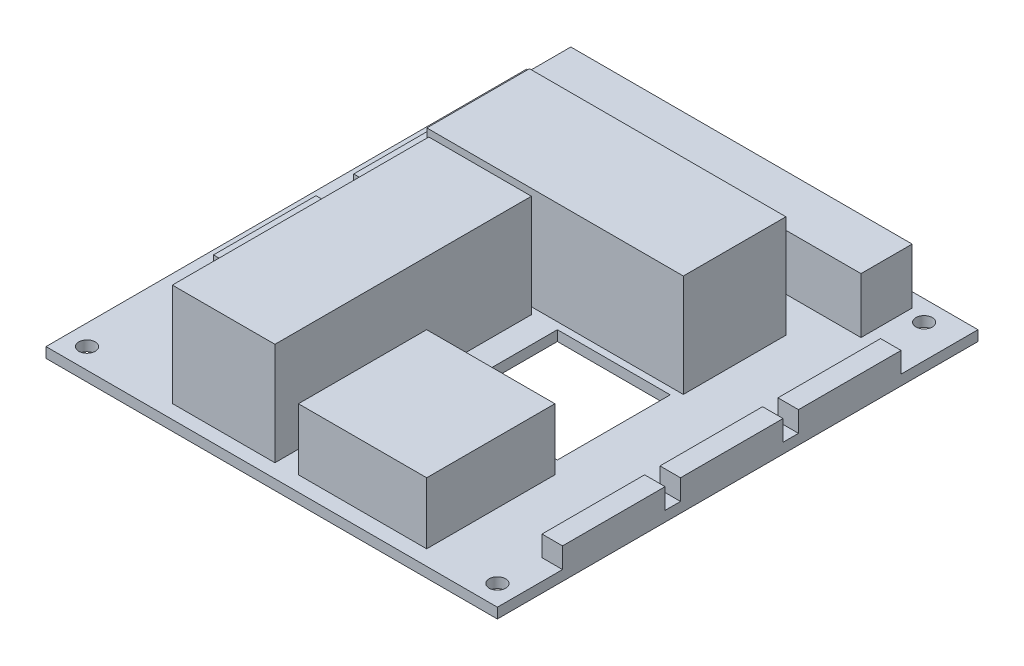
SolidWorks part; units mm, degrees
material "PBT General Purpose"
ref_plane "Front Plane" through (0, 0, 0) normal (0, 0, 1) x (1, 0, 0)
ref_plane "Top Plane" through (0, 0, 0) normal (0, 1, 0) x (1, 0, 0)
ref_plane "Right Plane" through (0, 0, 0) normal (1, 0, 0) x (0, 0, -1)
sketch "Sketch1" plane through (0, 0, 0) normal (0, 1, 0) x (1, 0, 0)
  line L1 (50, -50) -> (-50, -50) construction
  line L2 (50, -50) -> (50, 50) construction
  line L3 (50, 50) -> (-50, 50) construction
  line L4 (-50, -50) -> (-50, 50) construction
  line L5 (50, -50) -> (-50, 50) construction
  line L6 (50, 50) -> (-50, -50) construction
  line L7 (-50, 50) -> (-44, 50) construction
  line L8 (-50, 50) -> (-50, 44) construction
  line L9 (-50, 44) -> (-44, 44) construction
  line L10 (-44, 50) -> (-44, 44) construction
  line L11 (-50, -50) -> (-44, -50) construction
  line L12 (-50, -50) -> (-50, -44) construction
  line L13 (-50, -44) -> (-44, -44) construction
  line L14 (-44, -50) -> (-44, -44) construction
  line L15 (50, -50) -> (44, -50) construction
  line L16 (50, -50) -> (50, -44) construction
  line L17 (50, -44) -> (44, -44) construction
  line L18 (44, -50) -> (44, -44) construction
  line L19 (50, 50) -> (44, 50) construction
  line L20 (50, 50) -> (50, 44) construction
  line L21 (50, 44) -> (44, 44) construction
  line L22 (44, 50) -> (44, 44) construction
  line L25 (-32.625, 44.091) -> (33.923, 44.091) construction
  line L26 (-32.625, 44.091) -> (-32.625, 34.112) construction
  line L27 (-32.625, 34.112) -> (33.923, 34.112) construction
  line L28 (33.923, 44.091) -> (33.923, 34.112) construction
  line L30 (-50, 50) -> (-35, 50)
  line L31 (-50, 50) -> (-50, 48)
  line L32 (-50, 48) -> (-35, 48)
  line L33 (-35, 50) -> (-35, 48)
  line L34 (-50, 50) -> (-48, 50)
  line L35 (-50, 50) -> (-50, 35)
  line L36 (-50, 35) -> (-48, 35)
  line L37 (-48, 50) -> (-48, 35)
  line L38 (50, 50) -> (35, 50)
  line L39 (50, 50) -> (50, 48)
  line L40 (50, 48) -> (35, 48)
  line L41 (35, 50) -> (35, 48)
  line L42 (50, 50) -> (48, 50)
  line L43 (50, 50) -> (50, 35)
  line L44 (50, 35) -> (48, 35)
  line L45 (48, 50) -> (48, 35)
  line L46 (50, -50) -> (48, -50)
  line L47 (50, -50) -> (50, -35)
  line L48 (50, -35) -> (48, -35)
  line L49 (48, -50) -> (48, -35)
  line L50 (50, -50) -> (35, -50)
  line L51 (50, -50) -> (50, -48)
  line L52 (50, -48) -> (35, -48)
  line L53 (35, -50) -> (35, -48)
  line L54 (-50, -50) -> (-35, -50)
  line L55 (-50, -50) -> (-50, -48)
  line L56 (-50, -48) -> (-35, -48)
  line L57 (-35, -50) -> (-35, -48)
  line L58 (-50, -50) -> (-48, -50)
  line L59 (-50, -50) -> (-50, -35)
  line L60 (-50, -35) -> (-48, -35)
  line L61 (-48, -50) -> (-48, -35)
  line L62 (-33.125, 44.591) -> (-33.125, 33.612)
  line L63 (-33.125, 33.612) -> (34.423, 33.612)
  line L64 (34.423, 44.591) -> (34.423, 33.612)
  line L65 (-33.125, 44.591) -> (34.423, 44.591)
  circle A0 centre (-36.2, 42.85) radius 1.6
  circle A1 centre (37.5, 42.85) radius 1.6
  circle A2 centre (40, -42.85) radius 1.6
  circle A3 centre (-40, -42.85) radius 1.6
  point P0 (0, 0)
  point P5 (0, 0)
  point P6 (0, 0)
  dimension "D7" = 3.2
  dimension "D1" = 100
  dimension "D2" = 100
  dimension "D3" = 6
  dimension "D4" = 6
  dimension "D5" = 6
  dimension "D6" = 6
  dimension "D8" = 7.15
  dimension "D9" = 13.8
  dimension "D10" = 10
  dimension "D11" = 7.15
  dimension "D12" = 10
  dimension "D13" = 7.15
  dimension "D14" = 17.375
  dimension "D15" = 5.909
  dimension "D16" = 15.888
  dimension "D17" = 16.077
  dimension "D18" = 73.7
  dimension "D19" = 15
  dimension "D20" = 2
  dimension "D21" = 15
  dimension "D22" = 2
  dimension "D23" = 2
  dimension "D24" = 15
  dimension "D25" = 15
  dimension "D26" = 2
  dimension "D27" = 15
  dimension "D28" = 2
  dimension "D29" = 2
  dimension "D30" = 15
  dimension "D31" = 15
  dimension "D32" = 15
  dimension "D33" = 2
  dimension "D34" = 2
  dimension "D35" = 0.5
sketch "Sketch2" plane through (0, 0, 0) normal (0, 1, 0) x (1, 0, 0)
  line L0 (33.923, 44.091) -> (33.923, 34.112) construction
  line L1 (-32.625, 34.112) -> (33.923, 34.112) construction
  line L2 (-32.625, 44.091) -> (33.923, 44.091) construction
  line L3 (-32.625, 44.091) -> (-32.625, 34.112) construction
  line L4 (33.923, 44.091) -> (33.923, 34.112)
  line L5 (-32.625, 34.112) -> (33.923, 34.112)
  line L6 (-32.625, 44.091) -> (33.923, 44.091)
  line L7 (-32.625, 44.091) -> (-32.625, 34.112)
  line L8 (3, 5.85) -> (25, 5.85)
  line L9 (-22.0688, 5.85) -> (-2.0688, 5.85)
  line L10 (-22.0688, 5.85) -> (-22.0688, -44.15)
  line L11 (-22.0688, -44.15) -> (-2.0688, -44.15)
  line L12 (-2.0688, 5.85) -> (-2.0688, -44.15)
  line L13 (-23.7903, 27.1915) -> (26.2097, 27.1915)
  line L14 (-23.7903, 27.1915) -> (-23.7903, 7.1915)
  line L15 (-23.7903, 7.1915) -> (26.2097, 7.1915)
  line L16 (26.2097, 27.1915) -> (26.2097, 7.1915)
  line L17 (4, 4.85) -> (24, 4.85)
  line L18 (4, 4.85) -> (4, -15.15)
  line L19 (4, -15.15) -> (24, -15.15)
  line L20 (24, 4.85) -> (24, -15.15)
  line L21 (25, 5.85) -> (25, -16.15)
  line L22 (3, -16.15) -> (25, -16.15)
  line L23 (3, 5.85) -> (3, -16.15)
  line L24 (40, 8.85) -> (44, 8.85)
  line L25 (40, 31.85) -> (44, 31.85)
  line L26 (40, 31.85) -> (40, 11.85)
  line L27 (40, 11.85) -> (44, 11.85)
  line L28 (44, 31.85) -> (44, 11.85)
  line L29 (40, 8.85) -> (40, -11.15)
  line L30 (40, -11.15) -> (44, -11.15)
  line L31 (44, 8.85) -> (44, -11.15)
  line L32 (40, -14.15) -> (44, -14.15)
  line L33 (40, -14.15) -> (40, -34.15)
  line L34 (40, -34.15) -> (44, -34.15)
  line L35 (44, -14.15) -> (44, -34.15)
  line L37 (2.2571, -18.8919) -> (27.2571, -18.8919)
  line L38 (2.2571, -18.8919) -> (2.2571, -43.8919)
  line L39 (2.2571, -43.8919) -> (27.2571, -43.8919)
  line L40 (27.2571, -18.8919) -> (27.2571, -43.8919)
  line L41 (44, -46.85) -> (-44, -46.85) construction
  line L42 (44, -46.85) -> (44, 46.85) construction
  line L43 (44, 46.85) -> (-44, 46.85) construction
  line L44 (-44, -46.85) -> (-44, 46.85) construction
  line L45 (44, -46.85) -> (-44, 46.85) construction
  line L46 (44, 46.85) -> (-44, -46.85) construction
  circle A0 centre (40, -42.85) radius 1.6 construction
  circle A1 centre (-40, -42.85) radius 1.6 construction
  circle A2 centre (37.5, 42.85) radius 1.6 construction
  circle A3 centre (-36.2, 42.85) radius 1.6 construction
  circle A4 centre (40, -42.85) radius 1.6
  circle A5 centre (-40, -42.85) radius 1.6
  circle A6 centre (37.5, 42.85) radius 1.6
  circle A7 centre (-36.2, 42.85) radius 1.6
  point P32 (0, 0)
  dimension "D1" = 20
  dimension "D2" = 50
  dimension "D3" = 50
  dimension "D4" = 20
  dimension "D6" = 4
  dimension "D7" = 20
  dimension "D9" = 25
  dimension "D10" = 4
  dimension "D11" = 4
  dimension "D12" = 42
  dimension "D13" = 20
  dimension "D14" = 15
  dimension "D15" = 88
  dimension "D16" = 93.7
  dimension "D5" = 1
  dimension "D8" = 3
sketch "Sketch3" plane through (0, 0, 0) normal (0, 1, 0) x (1, 0, 0)
  line L0 (25, 5.85) -> (25, -16.15) construction
  line L1 (3, 5.85) -> (25, 5.85) construction
  line L2 (3, 5.85) -> (3, -16.15) construction
  line L3 (3, -16.15) -> (25, -16.15) construction
  line L4 (44, -46.85) -> (-44, -46.85) construction
  line L5 (44, -46.85) -> (44, 46.85) construction
  line L6 (44, 46.85) -> (-44, 46.85) construction
  line L7 (-44, -46.85) -> (-44, 46.85) construction
  line L8 (25, 5.85) -> (25, -16.15)
  line L9 (3, 5.85) -> (25, 5.85)
  line L10 (3, 5.85) -> (3, -16.15)
  line L11 (3, -16.15) -> (25, -16.15)
  line L12 (44, -46.85) -> (-44, -46.85)
  line L13 (44, -46.85) -> (44, 46.85)
  line L14 (44, 46.85) -> (-44, 46.85)
  line L15 (-44, -46.85) -> (-44, 46.85)
  circle A0 centre (-40, -42.85) radius 1.6 construction
  circle A1 centre (40, -42.85) radius 1.6 construction
  circle A2 centre (37.5, 42.85) radius 1.6 construction
  circle A3 centre (-36.2, 42.85) radius 1.6 construction
  circle A4 centre (-40, -42.85) radius 1.6
  circle A5 centre (40, -42.85) radius 1.6
  circle A6 centre (37.5, 42.85) radius 1.6
  circle A7 centre (-36.2, 42.85) radius 1.6
extrude "Boss-Extrude1" add sketch "Sketch3" along normal blind 2
sketch "Sketch4" plane through (0, 2, 0) normal (0, 1, 0) x (1, 0, 0)
  line L0 (-32.625, 44.091) -> (-32.625, 34.112) construction
  line L1 (-32.625, 34.112) -> (33.923, 34.112) construction
  line L2 (33.923, 44.091) -> (33.923, 34.112) construction
  line L3 (-32.625, 44.091) -> (33.923, 44.091) construction
  line L12 (-32.625, 44.091) -> (-32.625, 34.112)
  line L13 (-32.625, 34.112) -> (33.923, 34.112)
  line L14 (33.923, 44.091) -> (33.923, 34.112)
  line L15 (-32.625, 44.091) -> (33.923, 44.091)
extrude "Boss-Extrude2" add sketch "Sketch4" along normal blind 10.8 separate body
sketch "Sketch5" plane through (0, 2, 0) normal (0, -1, 0) x (1, 0, 0)
  line L0 (-32.625, -34.112) -> (33.923, -34.112) construction
  line L1 (-31.672, -35.065) -> (-31.037, -35.065)
  line L2 (-31.672, -35.065) -> (-31.672, -35.7)
  line L3 (-31.672, -35.7) -> (-31.037, -35.7)
  line L4 (-31.037, -35.065) -> (-31.037, -35.7)
  line L5 (-31.672, -35.065) -> (-31.037, -35.7) construction
  line L6 (-31.672, -35.7) -> (-31.037, -35.065) construction
  line L7 (-32.625, -44.091) -> (-32.625, -34.112) construction
  line L8 (-29.132, -35.065) -> (-28.497, -35.065)
  line L9 (-29.132, -35.065) -> (-29.132, -35.7)
  line L10 (-29.132, -35.7) -> (-28.497, -35.7)
  line L11 (-28.497, -35.065) -> (-28.497, -35.7)
  line L12 (-26.592, -35.065) -> (-25.957, -35.065)
  line L13 (-26.592, -35.065) -> (-26.592, -35.7)
  line L14 (-26.592, -35.7) -> (-25.957, -35.7)
  line L15 (-25.957, -35.065) -> (-25.957, -35.7)
  line L16 (-24.052, -35.065) -> (-23.417, -35.065)
  line L17 (-24.052, -35.065) -> (-24.052, -35.7)
  line L18 (-24.052, -35.7) -> (-23.417, -35.7)
  line L19 (-23.417, -35.065) -> (-23.417, -35.7)
  line L20 (-21.512, -35.065) -> (-20.877, -35.065)
  line L21 (-21.512, -35.065) -> (-21.512, -35.7)
  line L22 (-21.512, -35.7) -> (-20.877, -35.7)
  line L23 (-20.877, -35.065) -> (-20.877, -35.7)
  line L24 (-18.972, -35.065) -> (-18.337, -35.065)
  line L25 (-18.972, -35.065) -> (-18.972, -35.7)
  line L26 (-18.972, -35.7) -> (-18.337, -35.7)
  line L27 (-18.337, -35.065) -> (-18.337, -35.7)
  line L28 (-16.432, -35.065) -> (-15.797, -35.065)
  line L29 (-16.432, -35.065) -> (-16.432, -35.7)
  line L30 (-16.432, -35.7) -> (-15.797, -35.7)
  line L31 (-15.797, -35.065) -> (-15.797, -35.7)
  line L32 (-13.892, -35.065) -> (-13.257, -35.065)
  line L33 (-13.892, -35.065) -> (-13.892, -35.7)
  line L34 (-13.892, -35.7) -> (-13.257, -35.7)
  line L35 (-13.257, -35.065) -> (-13.257, -35.7)
  line L36 (-11.352, -35.065) -> (-10.717, -35.065)
  line L37 (-11.352, -35.065) -> (-11.352, -35.7)
  line L38 (-11.352, -35.7) -> (-10.717, -35.7)
  line L39 (-10.717, -35.065) -> (-10.717, -35.7)
  line L40 (-8.812, -35.065) -> (-8.177, -35.065)
  line L41 (-8.812, -35.065) -> (-8.812, -35.7)
  line L42 (-8.812, -35.7) -> (-8.177, -35.7)
  line L43 (-8.177, -35.065) -> (-8.177, -35.7)
  line L44 (-6.272, -35.065) -> (-5.637, -35.065)
  line L45 (-6.272, -35.065) -> (-6.272, -35.7)
  line L46 (-6.272, -35.7) -> (-5.637, -35.7)
  line L47 (-5.637, -35.065) -> (-5.637, -35.7)
  line L48 (-3.732, -35.065) -> (-3.097, -35.065)
  line L49 (-3.732, -35.065) -> (-3.732, -35.7)
  line L50 (-3.732, -35.7) -> (-3.097, -35.7)
  line L51 (-3.097, -35.065) -> (-3.097, -35.7)
  line L52 (-1.192, -35.065) -> (-0.557, -35.065)
  line L53 (-1.192, -35.065) -> (-1.192, -35.7)
  line L54 (-1.192, -35.7) -> (-0.557, -35.7)
  line L55 (-0.557, -35.065) -> (-0.557, -35.7)
  line L56 (1.348, -35.065) -> (1.983, -35.065)
  line L57 (1.348, -35.065) -> (1.348, -35.7)
  line L58 (1.348, -35.7) -> (1.983, -35.7)
  line L59 (1.983, -35.065) -> (1.983, -35.7)
  line L60 (3.888, -35.065) -> (4.523, -35.065)
  line L61 (3.888, -35.065) -> (3.888, -35.7)
  line L62 (3.888, -35.7) -> (4.523, -35.7)
  line L63 (4.523, -35.065) -> (4.523, -35.7)
  line L64 (6.428, -35.065) -> (7.063, -35.065)
  line L65 (6.428, -35.065) -> (6.428, -35.7)
  line L66 (6.428, -35.7) -> (7.063, -35.7)
  line L67 (7.063, -35.065) -> (7.063, -35.7)
  line L68 (8.968, -35.065) -> (9.603, -35.065)
  line L69 (8.968, -35.065) -> (8.968, -35.7)
  line L70 (8.968, -35.7) -> (9.603, -35.7)
  line L71 (9.603, -35.065) -> (9.603, -35.7)
  line L72 (11.508, -35.065) -> (12.143, -35.065)
  line L73 (11.508, -35.065) -> (11.508, -35.7)
  line L74 (11.508, -35.7) -> (12.143, -35.7)
  line L75 (12.143, -35.065) -> (12.143, -35.7)
  line L76 (14.048, -35.065) -> (14.683, -35.065)
  line L77 (14.048, -35.065) -> (14.048, -35.7)
  line L78 (14.048, -35.7) -> (14.683, -35.7)
  line L79 (14.683, -35.065) -> (14.683, -35.7)
  line L80 (16.588, -35.065) -> (17.223, -35.065)
  line L81 (16.588, -35.065) -> (16.588, -35.7)
  line L82 (16.588, -35.7) -> (17.223, -35.7)
  line L83 (17.223, -35.065) -> (17.223, -35.7)
  line L84 (19.128, -35.065) -> (19.763, -35.065)
  line L85 (19.128, -35.065) -> (19.128, -35.7)
  line L86 (19.128, -35.7) -> (19.763, -35.7)
  line L87 (19.763, -35.065) -> (19.763, -35.7)
  line L88 (21.668, -35.065) -> (22.303, -35.065)
  line L89 (21.668, -35.065) -> (21.668, -35.7)
  line L90 (21.668, -35.7) -> (22.303, -35.7)
  line L91 (22.303, -35.065) -> (22.303, -35.7)
  line L92 (24.208, -35.065) -> (24.843, -35.065)
  line L93 (24.208, -35.065) -> (24.208, -35.7)
  line L94 (24.208, -35.7) -> (24.843, -35.7)
  line L95 (24.843, -35.065) -> (24.843, -35.7)
  line L96 (26.748, -35.065) -> (27.383, -35.065)
  line L97 (26.748, -35.065) -> (26.748, -35.7)
  line L98 (26.748, -35.7) -> (27.383, -35.7)
  line L99 (27.383, -35.065) -> (27.383, -35.7)
  line L100 (29.288, -35.065) -> (29.923, -35.065)
  line L101 (29.288, -35.065) -> (29.288, -35.7)
  line L102 (29.288, -35.7) -> (29.923, -35.7)
  line L103 (29.923, -35.065) -> (29.923, -35.7)
  line L104 (31.828, -35.065) -> (32.463, -35.065)
  line L105 (31.828, -35.065) -> (31.828, -35.7)
  line L106 (31.828, -35.7) -> (32.463, -35.7)
  line L107 (32.463, -35.065) -> (32.463, -35.7)
  line L164 (-29.132, -37.605) -> (-28.497, -37.605)
  line L165 (-29.132, -37.605) -> (-29.132, -38.24)
  line L166 (-29.132, -38.24) -> (-28.497, -38.24)
  line L167 (-28.497, -37.605) -> (-28.497, -38.24)
  line L168 (-26.592, -37.605) -> (-25.957, -37.605)
  line L169 (-26.592, -37.605) -> (-26.592, -38.24)
  line L170 (-26.592, -38.24) -> (-25.957, -38.24)
  line L171 (-25.957, -37.605) -> (-25.957, -38.24)
  line L172 (-24.052, -37.605) -> (-23.417, -37.605)
  line L173 (-24.052, -37.605) -> (-24.052, -38.24)
  line L174 (-24.052, -38.24) -> (-23.417, -38.24)
  line L175 (-23.417, -37.605) -> (-23.417, -38.24)
  line L176 (-21.512, -37.605) -> (-20.877, -37.605)
  line L177 (-21.512, -37.605) -> (-21.512, -38.24)
  line L178 (-21.512, -38.24) -> (-20.877, -38.24)
  line L179 (-20.877, -37.605) -> (-20.877, -38.24)
  line L180 (-18.972, -37.605) -> (-18.337, -37.605)
  line L181 (-18.972, -37.605) -> (-18.972, -38.24)
  line L182 (-18.972, -38.24) -> (-18.337, -38.24)
  line L183 (-18.337, -37.605) -> (-18.337, -38.24)
  line L184 (-16.432, -37.605) -> (-15.797, -37.605)
  line L185 (-16.432, -37.605) -> (-16.432, -38.24)
  line L186 (-16.432, -38.24) -> (-15.797, -38.24)
  line L187 (-15.797, -37.605) -> (-15.797, -38.24)
  line L188 (-13.892, -37.605) -> (-13.257, -37.605)
  line L189 (-13.892, -37.605) -> (-13.892, -38.24)
  line L190 (-13.892, -38.24) -> (-13.257, -38.24)
  line L191 (-13.257, -37.605) -> (-13.257, -38.24)
  line L192 (-11.352, -37.605) -> (-10.717, -37.605)
  line L193 (-11.352, -37.605) -> (-11.352, -38.24)
  line L194 (-11.352, -38.24) -> (-10.717, -38.24)
  line L195 (-10.717, -37.605) -> (-10.717, -38.24)
  line L196 (-8.812, -37.605) -> (-8.177, -37.605)
  line L197 (-8.812, -37.605) -> (-8.812, -38.24)
  line L198 (-8.812, -38.24) -> (-8.177, -38.24)
  line L199 (-8.177, -37.605) -> (-8.177, -38.24)
  line L200 (-6.272, -37.605) -> (-5.637, -37.605)
  line L201 (-6.272, -37.605) -> (-6.272, -38.24)
  line L202 (-6.272, -38.24) -> (-5.637, -38.24)
  line L203 (-5.637, -37.605) -> (-5.637, -38.24)
  line L204 (-3.732, -37.605) -> (-3.097, -37.605)
  line L205 (-3.732, -37.605) -> (-3.732, -38.24)
  line L206 (-3.732, -38.24) -> (-3.097, -38.24)
  line L207 (-3.097, -37.605) -> (-3.097, -38.24)
  line L208 (-1.192, -37.605) -> (-0.557, -37.605)
  line L209 (-1.192, -37.605) -> (-1.192, -38.24)
  line L210 (-1.192, -38.24) -> (-0.557, -38.24)
  line L211 (-0.557, -37.605) -> (-0.557, -38.24)
  line L212 (1.348, -37.605) -> (1.983, -37.605)
  line L213 (1.348, -37.605) -> (1.348, -38.24)
  line L214 (1.348, -38.24) -> (1.983, -38.24)
  line L215 (1.983, -37.605) -> (1.983, -38.24)
  line L216 (3.888, -37.605) -> (4.523, -37.605)
  line L217 (3.888, -37.605) -> (3.888, -38.24)
  line L218 (3.888, -38.24) -> (4.523, -38.24)
  line L219 (4.523, -37.605) -> (4.523, -38.24)
  line L220 (6.428, -37.605) -> (7.063, -37.605)
  line L221 (6.428, -37.605) -> (6.428, -38.24)
  line L222 (6.428, -38.24) -> (7.063, -38.24)
  line L223 (7.063, -37.605) -> (7.063, -38.24)
  line L224 (8.968, -37.605) -> (9.603, -37.605)
  line L225 (8.968, -37.605) -> (8.968, -38.24)
  line L226 (8.968, -38.24) -> (9.603, -38.24)
  line L227 (9.603, -37.605) -> (9.603, -38.24)
  line L228 (11.508, -37.605) -> (12.143, -37.605)
  line L229 (11.508, -37.605) -> (11.508, -38.24)
  line L230 (11.508, -38.24) -> (12.143, -38.24)
  line L231 (12.143, -37.605) -> (12.143, -38.24)
  line L232 (14.048, -37.605) -> (14.683, -37.605)
  line L233 (14.048, -37.605) -> (14.048, -38.24)
  line L234 (14.048, -38.24) -> (14.683, -38.24)
  line L235 (14.683, -37.605) -> (14.683, -38.24)
  line L236 (16.588, -37.605) -> (17.223, -37.605)
  line L237 (16.588, -37.605) -> (16.588, -38.24)
  line L238 (16.588, -38.24) -> (17.223, -38.24)
  line L239 (17.223, -37.605) -> (17.223, -38.24)
  line L240 (19.128, -37.605) -> (19.763, -37.605)
  line L241 (19.128, -37.605) -> (19.128, -38.24)
  line L242 (19.128, -38.24) -> (19.763, -38.24)
  line L243 (19.763, -37.605) -> (19.763, -38.24)
  line L244 (21.668, -37.605) -> (22.303, -37.605)
  line L245 (21.668, -37.605) -> (21.668, -38.24)
  line L246 (21.668, -38.24) -> (22.303, -38.24)
  line L247 (22.303, -37.605) -> (22.303, -38.24)
  line L248 (24.208, -37.605) -> (24.843, -37.605)
  line L249 (24.208, -37.605) -> (24.208, -38.24)
  line L250 (24.208, -38.24) -> (24.843, -38.24)
  line L251 (24.843, -37.605) -> (24.843, -38.24)
  line L252 (26.748, -37.605) -> (27.383, -37.605)
  line L253 (26.748, -37.605) -> (26.748, -38.24)
  line L254 (26.748, -38.24) -> (27.383, -38.24)
  line L255 (27.383, -37.605) -> (27.383, -38.24)
  line L256 (29.288, -37.605) -> (29.923, -37.605)
  line L257 (29.288, -37.605) -> (29.288, -38.24)
  line L258 (29.288, -38.24) -> (29.923, -38.24)
  line L259 (29.923, -37.605) -> (29.923, -38.24)
  line L260 (31.828, -37.605) -> (32.463, -37.605)
  line L261 (31.828, -37.605) -> (31.828, -38.24)
  line L262 (31.828, -38.24) -> (32.463, -38.24)
  line L263 (32.463, -37.605) -> (32.463, -38.24)
  line L320 (-29.132, -40.145) -> (-28.497, -40.145)
  line L321 (-29.132, -40.145) -> (-29.132, -40.78)
  line L322 (-29.132, -40.78) -> (-28.497, -40.78)
  line L323 (-28.497, -40.145) -> (-28.497, -40.78)
  line L324 (-26.592, -40.145) -> (-25.957, -40.145)
  line L325 (-26.592, -40.145) -> (-26.592, -40.78)
  line L326 (-26.592, -40.78) -> (-25.957, -40.78)
  line L327 (-25.957, -40.145) -> (-25.957, -40.78)
  line L328 (-24.052, -40.145) -> (-23.417, -40.145)
  line L329 (-24.052, -40.145) -> (-24.052, -40.78)
  line L330 (-24.052, -40.78) -> (-23.417, -40.78)
  line L331 (-23.417, -40.145) -> (-23.417, -40.78)
  line L332 (-21.512, -40.145) -> (-20.877, -40.145)
  line L333 (-21.512, -40.145) -> (-21.512, -40.78)
  line L334 (-21.512, -40.78) -> (-20.877, -40.78)
  line L335 (-20.877, -40.145) -> (-20.877, -40.78)
  line L336 (-18.972, -40.145) -> (-18.337, -40.145)
  line L337 (-18.972, -40.145) -> (-18.972, -40.78)
  line L338 (-18.972, -40.78) -> (-18.337, -40.78)
  line L339 (-18.337, -40.145) -> (-18.337, -40.78)
  line L340 (-16.432, -40.145) -> (-15.797, -40.145)
  line L341 (-16.432, -40.145) -> (-16.432, -40.78)
  line L342 (-16.432, -40.78) -> (-15.797, -40.78)
  line L343 (-15.797, -40.145) -> (-15.797, -40.78)
  line L344 (-13.892, -40.145) -> (-13.257, -40.145)
  line L345 (-13.892, -40.145) -> (-13.892, -40.78)
  line L346 (-13.892, -40.78) -> (-13.257, -40.78)
  line L347 (-13.257, -40.145) -> (-13.257, -40.78)
  line L348 (-11.352, -40.145) -> (-10.717, -40.145)
  line L349 (-11.352, -40.145) -> (-11.352, -40.78)
  line L350 (-11.352, -40.78) -> (-10.717, -40.78)
  line L351 (-10.717, -40.145) -> (-10.717, -40.78)
  line L352 (-8.812, -40.145) -> (-8.177, -40.145)
  line L353 (-8.812, -40.145) -> (-8.812, -40.78)
  line L354 (-8.812, -40.78) -> (-8.177, -40.78)
  line L355 (-8.177, -40.145) -> (-8.177, -40.78)
  line L356 (-6.272, -40.145) -> (-5.637, -40.145)
  line L357 (-6.272, -40.145) -> (-6.272, -40.78)
  line L358 (-6.272, -40.78) -> (-5.637, -40.78)
  line L359 (-5.637, -40.145) -> (-5.637, -40.78)
  line L360 (-3.732, -40.145) -> (-3.097, -40.145)
  line L361 (-3.732, -40.145) -> (-3.732, -40.78)
  line L362 (-3.732, -40.78) -> (-3.097, -40.78)
  line L363 (-3.097, -40.145) -> (-3.097, -40.78)
  line L364 (-1.192, -40.145) -> (-0.557, -40.145)
  line L365 (-1.192, -40.145) -> (-1.192, -40.78)
  line L366 (-1.192, -40.78) -> (-0.557, -40.78)
  line L367 (-0.557, -40.145) -> (-0.557, -40.78)
  line L368 (1.348, -40.145) -> (1.983, -40.145)
  line L369 (1.348, -40.145) -> (1.348, -40.78)
  line L370 (1.348, -40.78) -> (1.983, -40.78)
  line L371 (1.983, -40.145) -> (1.983, -40.78)
  line L372 (3.888, -40.145) -> (4.523, -40.145)
  line L373 (3.888, -40.145) -> (3.888, -40.78)
  line L374 (3.888, -40.78) -> (4.523, -40.78)
  line L375 (4.523, -40.145) -> (4.523, -40.78)
  line L376 (6.428, -40.145) -> (7.063, -40.145)
  line L377 (6.428, -40.145) -> (6.428, -40.78)
  line L378 (6.428, -40.78) -> (7.063, -40.78)
  line L379 (7.063, -40.145) -> (7.063, -40.78)
  line L380 (8.968, -40.145) -> (9.603, -40.145)
  line L381 (8.968, -40.145) -> (8.968, -40.78)
  line L382 (8.968, -40.78) -> (9.603, -40.78)
  line L383 (9.603, -40.145) -> (9.603, -40.78)
  line L384 (11.508, -40.145) -> (12.143, -40.145)
  line L385 (11.508, -40.145) -> (11.508, -40.78)
  line L386 (11.508, -40.78) -> (12.143, -40.78)
  line L387 (12.143, -40.145) -> (12.143, -40.78)
  line L388 (14.048, -40.145) -> (14.683, -40.145)
  line L389 (14.048, -40.145) -> (14.048, -40.78)
  line L390 (14.048, -40.78) -> (14.683, -40.78)
  line L391 (14.683, -40.145) -> (14.683, -40.78)
  line L392 (16.588, -40.145) -> (17.223, -40.145)
  line L393 (16.588, -40.145) -> (16.588, -40.78)
  line L394 (16.588, -40.78) -> (17.223, -40.78)
  line L395 (17.223, -40.145) -> (17.223, -40.78)
  line L396 (19.128, -40.145) -> (19.763, -40.145)
  line L397 (19.128, -40.145) -> (19.128, -40.78)
  line L398 (19.128, -40.78) -> (19.763, -40.78)
  line L399 (19.763, -40.145) -> (19.763, -40.78)
  line L400 (21.668, -40.145) -> (22.303, -40.145)
  line L401 (21.668, -40.145) -> (21.668, -40.78)
  line L402 (21.668, -40.78) -> (22.303, -40.78)
  line L403 (22.303, -40.145) -> (22.303, -40.78)
  line L404 (24.208, -40.145) -> (24.843, -40.145)
  line L405 (24.208, -40.145) -> (24.208, -40.78)
  line L406 (24.208, -40.78) -> (24.843, -40.78)
  line L407 (24.843, -40.145) -> (24.843, -40.78)
  line L408 (26.748, -40.145) -> (27.383, -40.145)
  line L409 (26.748, -40.145) -> (26.748, -40.78)
  line L410 (26.748, -40.78) -> (27.383, -40.78)
  line L411 (27.383, -40.145) -> (27.383, -40.78)
  line L412 (29.288, -40.145) -> (29.923, -40.145)
  line L413 (29.288, -40.145) -> (29.288, -40.78)
  line L414 (29.288, -40.78) -> (29.923, -40.78)
  line L415 (29.923, -40.145) -> (29.923, -40.78)
  line L416 (31.828, -40.145) -> (32.463, -40.145)
  line L417 (31.828, -40.145) -> (31.828, -40.78)
  line L418 (31.828, -40.78) -> (32.463, -40.78)
  line L419 (32.463, -40.145) -> (32.463, -40.78)
  line L476 (-29.132, -42.685) -> (-28.497, -42.685)
  line L477 (-29.132, -42.685) -> (-29.132, -43.32)
  line L478 (-29.132, -43.32) -> (-28.497, -43.32)
  line L479 (-28.497, -42.685) -> (-28.497, -43.32)
  line L480 (-26.592, -42.685) -> (-25.957, -42.685)
  line L481 (-26.592, -42.685) -> (-26.592, -43.32)
  line L482 (-26.592, -43.32) -> (-25.957, -43.32)
  line L483 (-25.957, -42.685) -> (-25.957, -43.32)
  line L484 (-24.052, -42.685) -> (-23.417, -42.685)
  line L485 (-24.052, -42.685) -> (-24.052, -43.32)
  line L486 (-24.052, -43.32) -> (-23.417, -43.32)
  line L487 (-23.417, -42.685) -> (-23.417, -43.32)
  line L488 (-21.512, -42.685) -> (-20.877, -42.685)
  line L489 (-21.512, -42.685) -> (-21.512, -43.32)
  line L490 (-21.512, -43.32) -> (-20.877, -43.32)
  line L491 (-20.877, -42.685) -> (-20.877, -43.32)
  line L492 (-18.972, -42.685) -> (-18.337, -42.685)
  line L493 (-18.972, -42.685) -> (-18.972, -43.32)
  line L494 (-18.972, -43.32) -> (-18.337, -43.32)
  line L495 (-18.337, -42.685) -> (-18.337, -43.32)
  line L496 (-16.432, -42.685) -> (-15.797, -42.685)
  line L497 (-16.432, -42.685) -> (-16.432, -43.32)
  line L498 (-16.432, -43.32) -> (-15.797, -43.32)
  line L499 (-15.797, -42.685) -> (-15.797, -43.32)
  line L500 (-13.892, -42.685) -> (-13.257, -42.685)
  line L501 (-13.892, -42.685) -> (-13.892, -43.32)
  line L502 (-13.892, -43.32) -> (-13.257, -43.32)
  line L503 (-13.257, -42.685) -> (-13.257, -43.32)
  line L504 (-11.352, -42.685) -> (-10.717, -42.685)
  line L505 (-11.352, -42.685) -> (-11.352, -43.32)
  line L506 (-11.352, -43.32) -> (-10.717, -43.32)
  line L507 (-10.717, -42.685) -> (-10.717, -43.32)
  line L508 (-8.812, -42.685) -> (-8.177, -42.685)
  line L509 (-8.812, -42.685) -> (-8.812, -43.32)
  line L510 (-8.812, -43.32) -> (-8.177, -43.32)
  line L511 (-8.177, -42.685) -> (-8.177, -43.32)
  line L512 (-6.272, -42.685) -> (-5.637, -42.685)
  line L513 (-6.272, -42.685) -> (-6.272, -43.32)
  line L514 (-6.272, -43.32) -> (-5.637, -43.32)
  line L515 (-5.637, -42.685) -> (-5.637, -43.32)
  line L516 (-3.732, -42.685) -> (-3.097, -42.685)
  line L517 (-3.732, -42.685) -> (-3.732, -43.32)
  line L518 (-3.732, -43.32) -> (-3.097, -43.32)
  line L519 (-3.097, -42.685) -> (-3.097, -43.32)
  line L520 (-1.192, -42.685) -> (-0.557, -42.685)
  line L521 (-1.192, -42.685) -> (-1.192, -43.32)
  line L522 (-1.192, -43.32) -> (-0.557, -43.32)
  line L523 (-0.557, -42.685) -> (-0.557, -43.32)
  line L524 (1.348, -42.685) -> (1.983, -42.685)
  line L525 (1.348, -42.685) -> (1.348, -43.32)
  line L526 (1.348, -43.32) -> (1.983, -43.32)
  line L527 (1.983, -42.685) -> (1.983, -43.32)
  line L528 (3.888, -42.685) -> (4.523, -42.685)
  line L529 (3.888, -42.685) -> (3.888, -43.32)
  line L530 (3.888, -43.32) -> (4.523, -43.32)
  line L531 (4.523, -42.685) -> (4.523, -43.32)
  line L532 (6.428, -42.685) -> (7.063, -42.685)
  line L533 (6.428, -42.685) -> (6.428, -43.32)
  line L534 (6.428, -43.32) -> (7.063, -43.32)
  line L535 (7.063, -42.685) -> (7.063, -43.32)
  line L536 (8.968, -42.685) -> (9.603, -42.685)
  line L537 (8.968, -42.685) -> (8.968, -43.32)
  line L538 (8.968, -43.32) -> (9.603, -43.32)
  line L539 (9.603, -42.685) -> (9.603, -43.32)
  line L540 (11.508, -42.685) -> (12.143, -42.685)
  line L541 (11.508, -42.685) -> (11.508, -43.32)
  line L542 (11.508, -43.32) -> (12.143, -43.32)
  line L543 (12.143, -42.685) -> (12.143, -43.32)
  line L544 (14.048, -42.685) -> (14.683, -42.685)
  line L545 (14.048, -42.685) -> (14.048, -43.32)
  line L546 (14.048, -43.32) -> (14.683, -43.32)
  line L547 (14.683, -42.685) -> (14.683, -43.32)
  line L548 (16.588, -42.685) -> (17.223, -42.685)
  line L549 (16.588, -42.685) -> (16.588, -43.32)
  line L550 (16.588, -43.32) -> (17.223, -43.32)
  line L551 (17.223, -42.685) -> (17.223, -43.32)
  line L552 (19.128, -42.685) -> (19.763, -42.685)
  line L553 (19.128, -42.685) -> (19.128, -43.32)
  line L554 (19.128, -43.32) -> (19.763, -43.32)
  line L555 (19.763, -42.685) -> (19.763, -43.32)
  line L556 (21.668, -42.685) -> (22.303, -42.685)
  line L557 (21.668, -42.685) -> (21.668, -43.32)
  line L558 (21.668, -43.32) -> (22.303, -43.32)
  line L559 (22.303, -42.685) -> (22.303, -43.32)
  line L560 (24.208, -42.685) -> (24.843, -42.685)
  line L561 (24.208, -42.685) -> (24.208, -43.32)
  line L562 (24.208, -43.32) -> (24.843, -43.32)
  line L563 (24.843, -42.685) -> (24.843, -43.32)
  line L564 (26.748, -42.685) -> (27.383, -42.685)
  line L565 (26.748, -42.685) -> (26.748, -43.32)
  line L566 (26.748, -43.32) -> (27.383, -43.32)
  line L567 (27.383, -42.685) -> (27.383, -43.32)
  line L568 (29.288, -42.685) -> (29.923, -42.685)
  line L569 (29.288, -42.685) -> (29.288, -43.32)
  line L570 (29.288, -43.32) -> (29.923, -43.32)
  line L571 (29.923, -42.685) -> (29.923, -43.32)
  line L572 (31.828, -42.685) -> (32.463, -42.685)
  line L573 (31.828, -42.685) -> (31.828, -43.32)
  line L574 (31.828, -43.32) -> (32.463, -43.32)
  line L575 (32.463, -42.685) -> (32.463, -43.32)
  line L632 (-31.672, -37.605) -> (-31.037, -37.605)
  line L633 (-31.672, -37.605) -> (-31.672, -38.24)
  line L634 (-31.672, -38.24) -> (-31.037, -38.24)
  line L635 (-31.037, -37.605) -> (-31.037, -38.24)
  line L636 (-31.672, -40.145) -> (-31.037, -40.145)
  line L637 (-31.672, -40.145) -> (-31.672, -40.78)
  line L638 (-31.672, -40.78) -> (-31.037, -40.78)
  line L639 (-31.037, -40.145) -> (-31.037, -40.78)
  line L640 (-31.672, -42.685) -> (-31.037, -42.685)
  line L641 (-31.672, -42.685) -> (-31.672, -43.32)
  line L642 (-31.672, -43.32) -> (-31.037, -43.32)
  line L643 (-31.037, -42.685) -> (-31.037, -43.32)
  line L644 (34.368, -35.065) -> (35.003, -35.065) [skipped]
  line L645 (34.368, -35.065) -> (34.368, -35.7) [skipped]
  line L646 (34.368, -35.7) -> (35.003, -35.7) [skipped]
  line L647 (35.003, -35.065) -> (35.003, -35.7) [skipped]
  line L648 (36.908, -35.065) -> (37.543, -35.065) [skipped]
  line L649 (36.908, -35.065) -> (36.908, -35.7) [skipped]
  line L650 (36.908, -35.7) -> (37.543, -35.7) [skipped]
  line L651 (37.543, -35.065) -> (37.543, -35.7) [skipped]
  line L652 (39.448, -35.065) -> (40.083, -35.065) [skipped]
  line L653 (39.448, -35.065) -> (39.448, -35.7) [skipped]
  line L654 (39.448, -35.7) -> (40.083, -35.7) [skipped]
  line L655 (40.083, -35.065) -> (40.083, -35.7) [skipped]
  line L656 (41.988, -35.065) -> (42.623, -35.065) [skipped]
  line L657 (41.988, -35.065) -> (41.988, -35.7) [skipped]
  line L658 (41.988, -35.7) -> (42.623, -35.7) [skipped]
  line L659 (42.623, -35.065) -> (42.623, -35.7) [skipped]
  line L660 (44.528, -35.065) -> (45.163, -35.065) [skipped]
  line L661 (44.528, -35.065) -> (44.528, -35.7) [skipped]
  line L662 (44.528, -35.7) -> (45.163, -35.7) [skipped]
  line L663 (45.163, -35.065) -> (45.163, -35.7) [skipped]
  line L664 (47.068, -35.065) -> (47.703, -35.065) [skipped]
  line L665 (47.068, -35.065) -> (47.068, -35.7) [skipped]
  line L666 (47.068, -35.7) -> (47.703, -35.7) [skipped]
  line L667 (47.703, -35.065) -> (47.703, -35.7) [skipped]
  line L668 (49.608, -35.065) -> (50.243, -35.065) [skipped]
  line L669 (49.608, -35.065) -> (49.608, -35.7) [skipped]
  line L670 (49.608, -35.7) -> (50.243, -35.7) [skipped]
  line L671 (50.243, -35.065) -> (50.243, -35.7) [skipped]
  line L672 (52.148, -35.065) -> (52.783, -35.065) [skipped]
  line L673 (52.148, -35.065) -> (52.148, -35.7) [skipped]
  line L674 (52.148, -35.7) -> (52.783, -35.7) [skipped]
  line L675 (52.783, -35.065) -> (52.783, -35.7) [skipped]
  line L676 (54.688, -35.065) -> (55.323, -35.065) [skipped]
  line L677 (54.688, -35.065) -> (54.688, -35.7) [skipped]
  line L678 (54.688, -35.7) -> (55.323, -35.7) [skipped]
  line L679 (55.323, -35.065) -> (55.323, -35.7) [skipped]
  line L680 (57.228, -35.065) -> (57.863, -35.065) [skipped]
  line L681 (57.228, -35.065) -> (57.228, -35.7) [skipped]
  line L682 (57.228, -35.7) -> (57.863, -35.7) [skipped]
  line L683 (57.863, -35.065) -> (57.863, -35.7) [skipped]
  line L684 (59.768, -35.065) -> (60.403, -35.065) [skipped]
  line L685 (59.768, -35.065) -> (59.768, -35.7) [skipped]
  line L686 (59.768, -35.7) -> (60.403, -35.7) [skipped]
  line L687 (60.403, -35.065) -> (60.403, -35.7) [skipped]
  line L688 (62.308, -35.065) -> (62.943, -35.065) [skipped]
  line L689 (62.308, -35.065) -> (62.308, -35.7) [skipped]
  line L690 (62.308, -35.7) -> (62.943, -35.7) [skipped]
  line L691 (62.943, -35.065) -> (62.943, -35.7) [skipped]
  line L692 (64.848, -35.065) -> (65.483, -35.065) [skipped]
  line L693 (64.848, -35.065) -> (64.848, -35.7) [skipped]
  line L694 (64.848, -35.7) -> (65.483, -35.7) [skipped]
  line L695 (65.483, -35.065) -> (65.483, -35.7) [skipped]
  line L696 (67.388, -35.065) -> (68.023, -35.065) [skipped]
  line L697 (67.388, -35.065) -> (67.388, -35.7) [skipped]
  line L698 (67.388, -35.7) -> (68.023, -35.7) [skipped]
  line L699 (68.023, -35.065) -> (68.023, -35.7) [skipped]
  line L700 (34.368, -37.605) -> (35.003, -37.605) [skipped]
  line L701 (34.368, -37.605) -> (34.368, -38.24) [skipped]
  line L702 (34.368, -38.24) -> (35.003, -38.24) [skipped]
  line L703 (35.003, -37.605) -> (35.003, -38.24) [skipped]
  line L704 (36.908, -37.605) -> (37.543, -37.605) [skipped]
  line L705 (36.908, -37.605) -> (36.908, -38.24) [skipped]
  line L706 (36.908, -38.24) -> (37.543, -38.24) [skipped]
  line L707 (37.543, -37.605) -> (37.543, -38.24) [skipped]
  line L708 (39.448, -37.605) -> (40.083, -37.605) [skipped]
  line L709 (39.448, -37.605) -> (39.448, -38.24) [skipped]
  line L710 (39.448, -38.24) -> (40.083, -38.24) [skipped]
  line L711 (40.083, -37.605) -> (40.083, -38.24) [skipped]
  line L712 (41.988, -37.605) -> (42.623, -37.605) [skipped]
  line L713 (41.988, -37.605) -> (41.988, -38.24) [skipped]
  line L714 (41.988, -38.24) -> (42.623, -38.24) [skipped]
  line L715 (42.623, -37.605) -> (42.623, -38.24) [skipped]
  line L716 (44.528, -37.605) -> (45.163, -37.605) [skipped]
  line L717 (44.528, -37.605) -> (44.528, -38.24) [skipped]
  line L718 (44.528, -38.24) -> (45.163, -38.24) [skipped]
  line L719 (45.163, -37.605) -> (45.163, -38.24) [skipped]
  line L720 (47.068, -37.605) -> (47.703, -37.605) [skipped]
  line L721 (47.068, -37.605) -> (47.068, -38.24) [skipped]
  line L722 (47.068, -38.24) -> (47.703, -38.24) [skipped]
  line L723 (47.703, -37.605) -> (47.703, -38.24) [skipped]
  line L724 (49.608, -37.605) -> (50.243, -37.605) [skipped]
  line L725 (49.608, -37.605) -> (49.608, -38.24) [skipped]
  line L726 (49.608, -38.24) -> (50.243, -38.24) [skipped]
  line L727 (50.243, -37.605) -> (50.243, -38.24) [skipped]
  line L728 (52.148, -37.605) -> (52.783, -37.605) [skipped]
  line L729 (52.148, -37.605) -> (52.148, -38.24) [skipped]
  line L730 (52.148, -38.24) -> (52.783, -38.24) [skipped]
  line L731 (52.783, -37.605) -> (52.783, -38.24) [skipped]
  line L732 (54.688, -37.605) -> (55.323, -37.605) [skipped]
  line L733 (54.688, -37.605) -> (54.688, -38.24) [skipped]
  line L734 (54.688, -38.24) -> (55.323, -38.24) [skipped]
  line L735 (55.323, -37.605) -> (55.323, -38.24) [skipped]
  line L736 (57.228, -37.605) -> (57.863, -37.605) [skipped]
  line L737 (57.228, -37.605) -> (57.228, -38.24) [skipped]
  line L738 (57.228, -38.24) -> (57.863, -38.24) [skipped]
  line L739 (57.863, -37.605) -> (57.863, -38.24) [skipped]
  line L740 (59.768, -37.605) -> (60.403, -37.605) [skipped]
  line L741 (59.768, -37.605) -> (59.768, -38.24) [skipped]
  line L742 (59.768, -38.24) -> (60.403, -38.24) [skipped]
  line L743 (60.403, -37.605) -> (60.403, -38.24) [skipped]
  line L744 (62.308, -37.605) -> (62.943, -37.605) [skipped]
  line L745 (62.308, -37.605) -> (62.308, -38.24) [skipped]
  line L746 (62.308, -38.24) -> (62.943, -38.24) [skipped]
  line L747 (62.943, -37.605) -> (62.943, -38.24) [skipped]
  line L748 (64.848, -37.605) -> (65.483, -37.605) [skipped]
  line L749 (64.848, -37.605) -> (64.848, -38.24) [skipped]
  line L750 (64.848, -38.24) -> (65.483, -38.24) [skipped]
  line L751 (65.483, -37.605) -> (65.483, -38.24) [skipped]
  line L752 (67.388, -37.605) -> (68.023, -37.605) [skipped]
  line L753 (67.388, -37.605) -> (67.388, -38.24) [skipped]
  line L754 (67.388, -38.24) -> (68.023, -38.24) [skipped]
  line L755 (68.023, -37.605) -> (68.023, -38.24) [skipped]
  line L756 (34.368, -40.145) -> (35.003, -40.145) [skipped]
  line L757 (34.368, -40.145) -> (34.368, -40.78) [skipped]
  line L758 (34.368, -40.78) -> (35.003, -40.78) [skipped]
  line L759 (35.003, -40.145) -> (35.003, -40.78) [skipped]
  line L760 (36.908, -40.145) -> (37.543, -40.145) [skipped]
  line L761 (36.908, -40.145) -> (36.908, -40.78) [skipped]
  line L762 (36.908, -40.78) -> (37.543, -40.78) [skipped]
  line L763 (37.543, -40.145) -> (37.543, -40.78) [skipped]
  line L764 (39.448, -40.145) -> (40.083, -40.145) [skipped]
  line L765 (39.448, -40.145) -> (39.448, -40.78) [skipped]
  line L766 (39.448, -40.78) -> (40.083, -40.78) [skipped]
  line L767 (40.083, -40.145) -> (40.083, -40.78) [skipped]
  line L768 (41.988, -40.145) -> (42.623, -40.145) [skipped]
  line L769 (41.988, -40.145) -> (41.988, -40.78) [skipped]
  line L770 (41.988, -40.78) -> (42.623, -40.78) [skipped]
  line L771 (42.623, -40.145) -> (42.623, -40.78) [skipped]
  line L772 (44.528, -40.145) -> (45.163, -40.145) [skipped]
  line L773 (44.528, -40.145) -> (44.528, -40.78) [skipped]
  line L774 (44.528, -40.78) -> (45.163, -40.78) [skipped]
  line L775 (45.163, -40.145) -> (45.163, -40.78) [skipped]
  line L776 (47.068, -40.145) -> (47.703, -40.145) [skipped]
  line L777 (47.068, -40.145) -> (47.068, -40.78) [skipped]
  line L778 (47.068, -40.78) -> (47.703, -40.78) [skipped]
  line L779 (47.703, -40.145) -> (47.703, -40.78) [skipped]
  line L780 (49.608, -40.145) -> (50.243, -40.145) [skipped]
  line L781 (49.608, -40.145) -> (49.608, -40.78) [skipped]
  line L782 (49.608, -40.78) -> (50.243, -40.78) [skipped]
  line L783 (50.243, -40.145) -> (50.243, -40.78) [skipped]
  line L784 (52.148, -40.145) -> (52.783, -40.145) [skipped]
  line L785 (52.148, -40.145) -> (52.148, -40.78) [skipped]
  line L786 (52.148, -40.78) -> (52.783, -40.78) [skipped]
  line L787 (52.783, -40.145) -> (52.783, -40.78) [skipped]
  line L788 (54.688, -40.145) -> (55.323, -40.145) [skipped]
  line L789 (54.688, -40.145) -> (54.688, -40.78) [skipped]
  line L790 (54.688, -40.78) -> (55.323, -40.78) [skipped]
  line L791 (55.323, -40.145) -> (55.323, -40.78) [skipped]
  line L792 (57.228, -40.145) -> (57.863, -40.145) [skipped]
  line L793 (57.228, -40.145) -> (57.228, -40.78) [skipped]
  line L794 (57.228, -40.78) -> (57.863, -40.78) [skipped]
  line L795 (57.863, -40.145) -> (57.863, -40.78) [skipped]
  line L796 (59.768, -40.145) -> (60.403, -40.145) [skipped]
  line L797 (59.768, -40.145) -> (59.768, -40.78) [skipped]
  line L798 (59.768, -40.78) -> (60.403, -40.78) [skipped]
  line L799 (60.403, -40.145) -> (60.403, -40.78) [skipped]
  line L800 (62.308, -40.145) -> (62.943, -40.145) [skipped]
  line L801 (62.308, -40.145) -> (62.308, -40.78) [skipped]
  line L802 (62.308, -40.78) -> (62.943, -40.78) [skipped]
  line L803 (62.943, -40.145) -> (62.943, -40.78) [skipped]
  line L804 (64.848, -40.145) -> (65.483, -40.145) [skipped]
  line L805 (64.848, -40.145) -> (64.848, -40.78) [skipped]
  line L806 (64.848, -40.78) -> (65.483, -40.78) [skipped]
  line L807 (65.483, -40.145) -> (65.483, -40.78) [skipped]
  line L808 (67.388, -40.145) -> (68.023, -40.145) [skipped]
  line L809 (67.388, -40.145) -> (67.388, -40.78) [skipped]
  line L810 (67.388, -40.78) -> (68.023, -40.78) [skipped]
  line L811 (68.023, -40.145) -> (68.023, -40.78) [skipped]
  line L812 (34.368, -42.685) -> (35.003, -42.685) [skipped]
  line L813 (34.368, -42.685) -> (34.368, -43.32) [skipped]
  line L814 (34.368, -43.32) -> (35.003, -43.32) [skipped]
  line L815 (35.003, -42.685) -> (35.003, -43.32) [skipped]
  line L816 (36.908, -42.685) -> (37.543, -42.685) [skipped]
  line L817 (36.908, -42.685) -> (36.908, -43.32) [skipped]
  line L818 (36.908, -43.32) -> (37.543, -43.32) [skipped]
  line L819 (37.543, -42.685) -> (37.543, -43.32) [skipped]
  line L820 (39.448, -42.685) -> (40.083, -42.685) [skipped]
  line L821 (39.448, -42.685) -> (39.448, -43.32) [skipped]
  line L822 (39.448, -43.32) -> (40.083, -43.32) [skipped]
  line L823 (40.083, -42.685) -> (40.083, -43.32) [skipped]
  line L824 (41.988, -42.685) -> (42.623, -42.685) [skipped]
  line L825 (41.988, -42.685) -> (41.988, -43.32) [skipped]
  line L826 (41.988, -43.32) -> (42.623, -43.32) [skipped]
  line L827 (42.623, -42.685) -> (42.623, -43.32) [skipped]
  line L828 (44.528, -42.685) -> (45.163, -42.685) [skipped]
  line L829 (44.528, -42.685) -> (44.528, -43.32) [skipped]
  line L830 (44.528, -43.32) -> (45.163, -43.32) [skipped]
  line L831 (45.163, -42.685) -> (45.163, -43.32) [skipped]
  line L832 (47.068, -42.685) -> (47.703, -42.685) [skipped]
  line L833 (47.068, -42.685) -> (47.068, -43.32) [skipped]
  line L834 (47.068, -43.32) -> (47.703, -43.32) [skipped]
  line L835 (47.703, -42.685) -> (47.703, -43.32) [skipped]
  line L836 (49.608, -42.685) -> (50.243, -42.685) [skipped]
  line L837 (49.608, -42.685) -> (49.608, -43.32) [skipped]
  line L838 (49.608, -43.32) -> (50.243, -43.32) [skipped]
  line L839 (50.243, -42.685) -> (50.243, -43.32) [skipped]
  line L840 (52.148, -42.685) -> (52.783, -42.685) [skipped]
  line L841 (52.148, -42.685) -> (52.148, -43.32) [skipped]
  line L842 (52.148, -43.32) -> (52.783, -43.32) [skipped]
  line L843 (52.783, -42.685) -> (52.783, -43.32) [skipped]
  line L844 (54.688, -42.685) -> (55.323, -42.685) [skipped]
  line L845 (54.688, -42.685) -> (54.688, -43.32) [skipped]
  line L846 (54.688, -43.32) -> (55.323, -43.32) [skipped]
  line L847 (55.323, -42.685) -> (55.323, -43.32) [skipped]
  line L848 (57.228, -42.685) -> (57.863, -42.685) [skipped]
  line L849 (57.228, -42.685) -> (57.228, -43.32) [skipped]
  line L850 (57.228, -43.32) -> (57.863, -43.32) [skipped]
  line L851 (57.863, -42.685) -> (57.863, -43.32) [skipped]
  line L852 (59.768, -42.685) -> (60.403, -42.685) [skipped]
  line L853 (59.768, -42.685) -> (59.768, -43.32) [skipped]
  line L854 (59.768, -43.32) -> (60.403, -43.32) [skipped]
  line L855 (60.403, -42.685) -> (60.403, -43.32) [skipped]
  line L856 (62.308, -42.685) -> (62.943, -42.685) [skipped]
  line L857 (62.308, -42.685) -> (62.308, -43.32) [skipped]
  line L858 (62.308, -43.32) -> (62.943, -43.32) [skipped]
  line L859 (62.943, -42.685) -> (62.943, -43.32) [skipped]
  line L860 (64.848, -42.685) -> (65.483, -42.685) [skipped]
  line L861 (64.848, -42.685) -> (64.848, -43.32) [skipped]
  line L862 (64.848, -43.32) -> (65.483, -43.32) [skipped]
  line L863 (65.483, -42.685) -> (65.483, -43.32) [skipped]
  line L864 (67.388, -42.685) -> (68.023, -42.685) [skipped]
  line L865 (67.388, -42.685) -> (67.388, -43.32) [skipped]
  line L866 (67.388, -43.32) -> (68.023, -43.32) [skipped]
  line L867 (68.023, -42.685) -> (68.023, -43.32) [skipped]
  point P0 (-31.3545, -35.3825)
  dimension "D1" = 0.635
  dimension "D2" = 0.953
  dimension "D3" = 0.953
  dimension "D4" = 40
  dimension "D5" = 4
sketch "Sketch6" plane through (0, 2, 0) normal (0, 1, 0) x (1, 0, 0)
  line L0 (-22.0688, -44.15) -> (-2.0688, -44.15) construction
  line L1 (-22.0688, 5.85) -> (-22.0688, -44.15) construction
  line L2 (-2.0688, 5.85) -> (-2.0688, -44.15) construction
  line L3 (-22.0688, 5.85) -> (-2.0688, 5.85) construction
  line L12 (-23.7903, 27.1915) -> (-23.7903, 7.1915) construction
  line L13 (-23.7903, 7.1915) -> (26.2097, 7.1915) construction
  line L14 (26.2097, 27.1915) -> (26.2097, 7.1915) construction
  line L15 (-23.7903, 27.1915) -> (26.2097, 27.1915) construction
  line L16 (-22.0688, -44.15) -> (-2.0688, -44.15)
  line L17 (-22.0688, 5.85) -> (-22.0688, -44.15)
  line L18 (-2.0688, 5.85) -> (-2.0688, -44.15)
  line L19 (-22.0688, 5.85) -> (-2.0688, 5.85)
  line L20 (-23.7903, 27.1915) -> (-23.7903, 7.1915)
  line L21 (-23.7903, 7.1915) -> (26.2097, 7.1915)
  line L22 (26.2097, 27.1915) -> (26.2097, 7.1915)
  line L23 (-23.7903, 27.1915) -> (26.2097, 27.1915)
extrude "Boss-Extrude3" add sketch "Sketch6" along normal blind 20
sketch "Sketch8" plane through (0, 2, 0) normal (0, 1, 0) x (1, 0, 0)
  line L0 (27.2571, -18.8919) -> (27.2571, -43.8919) construction
  line L1 (2.2571, -43.8919) -> (27.2571, -43.8919) construction
  line L2 (2.2571, -18.8919) -> (2.2571, -43.8919) construction
  line L3 (2.2571, -18.8919) -> (27.2571, -18.8919) construction
  line L4 (27.2571, -18.8919) -> (27.2571, -43.8919)
  line L5 (2.2571, -43.8919) -> (27.2571, -43.8919)
  line L6 (2.2571, -18.8919) -> (2.2571, -43.8919)
  line L7 (2.2571, -18.8919) -> (27.2571, -18.8919)
extrude "Boss-Extrude4" add sketch "Sketch8" along normal blind 12
sketch "Sketch9" plane through (0, 2, 0) normal (0, 1, 0) x (1, 0, 0)
  line L0 (44, -14.15) -> (44, -34.15) construction
  line L1 (40, -34.15) -> (44, -34.15) construction
  line L2 (40, -14.15) -> (40, -34.15) construction
  line L3 (40, -14.15) -> (44, -14.15) construction
  line L4 (40, -11.15) -> (44, -11.15) construction
  line L5 (44, 8.85) -> (44, -11.15) construction
  line L6 (40, 8.85) -> (40, -11.15) construction
  line L7 (40, 8.85) -> (44, 8.85) construction
  line L8 (40, 11.85) -> (44, 11.85) construction
  line L9 (44, 31.85) -> (44, 11.85) construction
  line L10 (40, 31.85) -> (44, 31.85) construction
  line L11 (40, 31.85) -> (40, 11.85) construction
  line L12 (44, -14.15) -> (44, -34.15)
  line L13 (40, -34.15) -> (44, -34.15)
  line L14 (40, -14.15) -> (40, -34.15)
  line L15 (40, -14.15) -> (44, -14.15)
  line L16 (40, -11.15) -> (44, -11.15)
  line L17 (44, 8.85) -> (44, -11.15)
  line L18 (40, 8.85) -> (40, -11.15)
  line L19 (40, 8.85) -> (44, 8.85)
  line L20 (40, 11.85) -> (44, 11.85)
  line L21 (44, 31.85) -> (44, 11.85)
  line L22 (40, 31.85) -> (44, 31.85)
  line L23 (40, 31.85) -> (40, 11.85)
  line L33 (-39.1518, 28.2923) -> (-35.1518, 28.2923)
  line L34 (-39.1518, 28.2923) -> (-39.1518, 8.2923)
  line L35 (-39.1518, 8.2923) -> (-35.1518, 8.2923)
  line L36 (-35.1518, 28.2923) -> (-35.1518, 8.2923)
  line L37 (-39.1518, 0.9482) -> (-35.1518, 0.9482)
  line L38 (-39.1518, 0.9482) -> (-39.1518, -19.0518)
  line L39 (-39.1518, -19.0518) -> (-35.1518, -19.0518)
  line L40 (-35.1518, 0.9482) -> (-35.1518, -19.0518)
extrude "Boss-Extrude5" add sketch "Sketch9" along normal blind 4
extrude "Boss-Extrude6" add sketch "Sketch5" along normal blind 12
